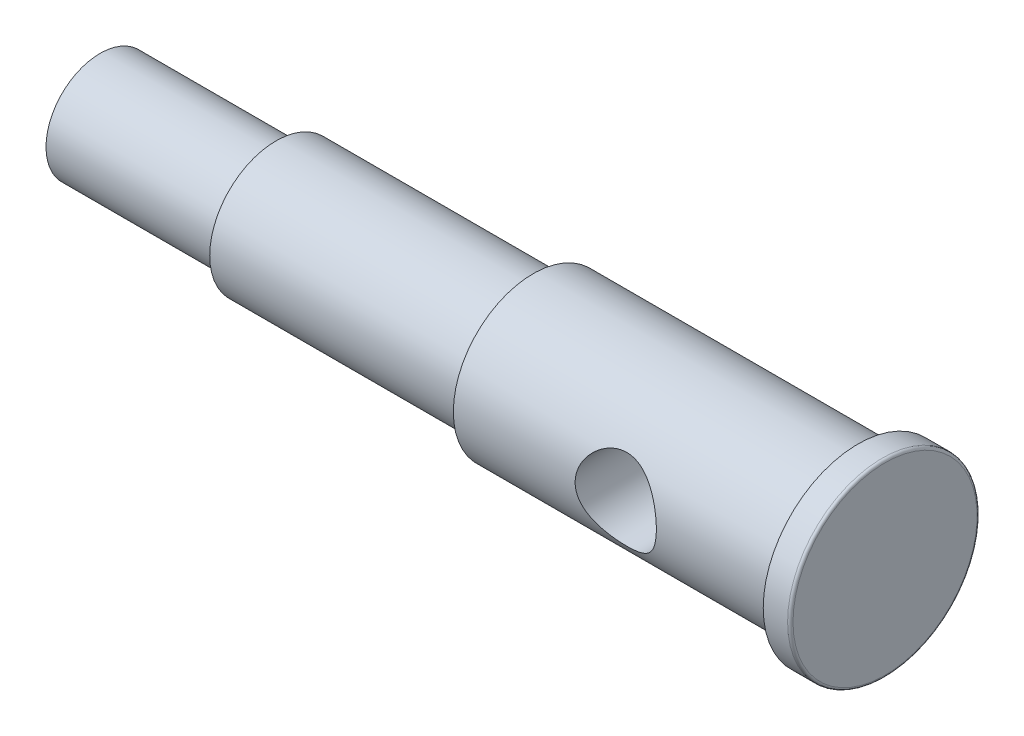
SolidWorks part; units mm, degrees
ref_plane "Front Plane" through (0, 0, 0) normal (0, 0, 1) x (1, 0, 0)
ref_plane "Top Plane" through (0, 0, 0) normal (0, 1, 0) x (1, 0, 0)
ref_plane "Right Plane" through (0, 0, 0) normal (1, 0, 0) x (0, 0, -1)
sketch "Sketch1" plane through (0, 0, 0) normal (0, 1, 0) x (1, 0, 0)
  line L0 (-33.9236, 0) -> (4.4287, 0) construction
  line L1 (-29, 0) -> (0, 0)
  line L2 (0, 0) -> (0, 3.5)
  line L3 (0, 3.5) -> (-1, 3.5)
  line L4 (-1, 3.5) -> (-1, 2.95)
  line L5 (-1, 2.95) -> (-13, 2.95)
  line L6 (-13, 2.95) -> (-13, 2.45)
  line L7 (-13, 2.45) -> (-22.5, 2.45)
  line L8 (-22.5, 2.45) -> (-22.5, 2)
  line L9 (-22.5, 2) -> (-29, 2)
  line L10 (-29, 2) -> (-29, 0)
  dimension "D1" = 29
  dimension "D2" = 1
  dimension "D3" = 13
  dimension "D4" = 22.5
  dimension "D5" = 7
  dimension "D6" = 5.9
  dimension "D7" = 4.9
  dimension "D8" = 4
revolve "Revolve1" add sketch "Sketch1" angle 360 about L0
cosmetic thread "Cosmetic Thread1" parameters "D2"=3.242
sketch "Sketch2" plane through (0, 0, 0) normal (0, 0, 1) x (1, 0, 0)
  line L0 (-1, 2.95) -> (-1, -2.95) construction
  circle A0 centre (-7, 0) radius 1.5
  dimension "D1" = 3
  dimension "D2" = 6
extrude "Cut-Extrude1" cut sketch "Sketch2" against normal up to next and the other way up to next
fillet "Fillet1" radius 0.1 1 edges at (0, 0, 3.5)
